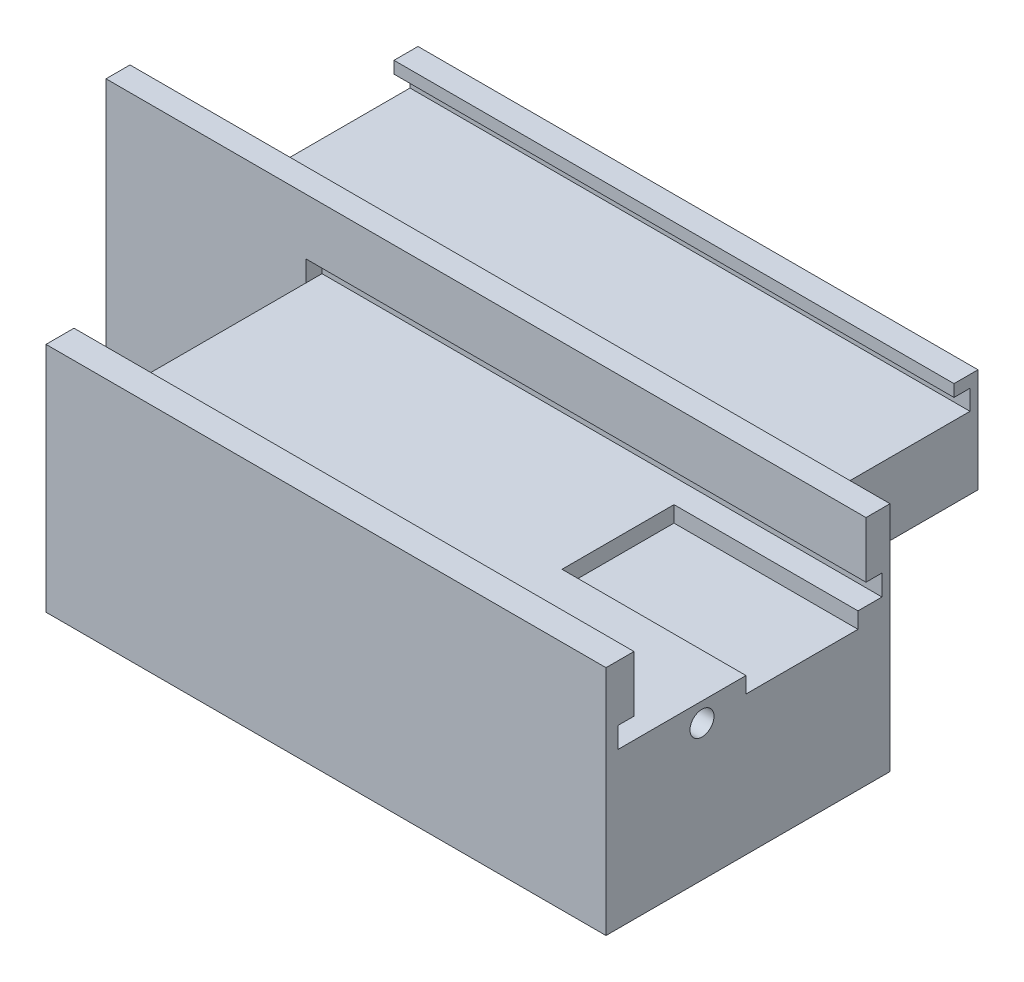
SolidWorks part; units mm, degrees
ref_plane "Front Plane" through (0, 0, 0) normal (0, 0, 1) x (1, 0, 0)
ref_plane "Top Plane" through (0, 0, 0) normal (0, 1, 0) x (1, 0, 0)
ref_plane "Right Plane" through (0, 0, 0) normal (1, 0, 0) x (0, 0, -1)
sketch "Sketch1" plane through (-29.7596, 0, 0) normal (-1, 0, 0) x (0, 0, 1)
  line L0 (-16.3556, -2.2828) -> (-18.3556, -2.2828)
  line L1 (-18.3556, -2.2828) -> (-18.3556, -4.7828)
  line L2 (-18.3556, -4.7828) -> (18.6444, -4.7828)
  line L3 (18.6444, -4.7828) -> (18.6444, -2.2828)
  line L4 (18.6444, -2.2828) -> (16.6444, -2.2828)
  line L10 (50.6443, 5.6172) -> (17.6444, 5.6172)
  line L16 (52.1443, -13.7828) -> (-19.3556, -13.7828)
  line L17 (-19.3556, -13.7828) -> (-19.3556, -0.7828)
  line L18 (-19.3556, -0.7828) -> (-16.3556, -0.7828)
  line L19 (-16.3556, -0.7828) -> (-16.3556, -2.2828)
  line L20 (-15.8556, 15.2172) -> (-15.8556, -2.7828) construction
  line L21 (16.6444, -2.2828) -> (16.6444, 15.2172)
  line L22 (-16.3556, -2.2828) -> (-16.3556, -2.7828) construction
  line L23 (-17.8556, -2.7828) -> (18.1444, -2.7828) construction
  line L24 (-12.9176, -4.2828) -> (-12.9176, -4.7828) construction
  line L25 (-17.8556, -4.2828) -> (18.1444, -4.2828) construction
  line L26 (-18.3556, -3.5328) -> (-17.8556, -3.5328) construction
  line L27 (-17.8556, -2.7828) -> (-17.8556, -4.2828) construction
  line L28 (18.1444, -3.5328) -> (18.6444, -3.5328) construction
  line L29 (18.1444, -2.7828) -> (18.1444, -4.2828) construction
  line L30 (17.1704, -2.2828) -> (17.1704, -2.7828) construction
  line L31 (-16.3556, -0.7705) -> (-15.8556, -0.7705) construction
  line L32 (16.1444, 1.5351) -> (16.6444, 1.5351) construction
  line L33 (16.1444, 15.2172) -> (16.1444, -2.7828) construction
  line L34 (19.2879, 8.2172) -> (19.2879, 7.7172) construction
  line L35 (18.1444, 7.7172) -> (50.1443, 7.7172) construction
  line L36 (50.6443, 5.6172) -> (50.6443, 8.2172)
  line L38 (24.3346, 6.1172) -> (24.3346, 5.6172) construction
  line L39 (50.1443, 6.1172) -> (18.1444, 6.1172) construction
  line L40 (48.848, 8.2172) -> (48.848, 7.7172) construction
  line L41 (16.6444, 15.2172) -> (19.6444, 15.2172)
  line L42 (19.6444, 15.2172) -> (19.6444, 8.2172)
  line L43 (19.6444, 8.2172) -> (17.6444, 8.2172)
  line L44 (17.6444, 8.2172) -> (17.6444, 5.6172)
  line L45 (18.1444, 6.6167) -> (17.6444, 6.6167) construction
  line L46 (18.1444, 6.1172) -> (18.1444, 7.7172) construction
  line L47 (50.6443, 8.2172) -> (48.6443, 8.2172)
  line L48 (48.6443, 8.2172) -> (48.6443, 15.2172)
  line L49 (48.6443, 15.2172) -> (52.1443, 15.2172)
  line L50 (52.1443, 15.2172) -> (52.1443, -13.7828)
  line L51 (50.1443, 6.4526) -> (50.6443, 6.4526) construction
  line L52 (50.1443, 6.1172) -> (50.1443, 7.7172) construction
  dimension "D1" = 0.5
  dimension "D2" = 1.5
  dimension "D3" = 1
  dimension "D4" = 0.5
  dimension "D5" = 9
  dimension "D6" = 29
  dimension "D7" = 1.5
extrude "Boss-Extrude1" add sketch "Sketch1" against normal up to surface (94.9999 mm away)
sketch "Sketch2" plane through (0, 5.6172, 0) normal (0, 1, 0) x (1, 0, 0)
  line L0 (65.2403, -50.6443) -> (65.2403, -17.6444) construction
  line L1 (65.2403, -20.6444) -> (42.2403, -20.6444)
  line L2 (65.2403, -20.6444) -> (65.2403, -34.6444)
  line L3 (65.2403, -34.6444) -> (42.2403, -34.6444)
  line L4 (42.2403, -20.6444) -> (42.2403, -34.6444)
  line L5 (65.2403, -18.6444) -> (-29.7596, -18.6444) construction
  dimension "D1" = 2
  dimension "D2" = 23
  dimension "D3" = 14
extrude "Cut-Extrude1" cut sketch "Sketch2" against normal blind 2
sketch "Sketch4" plane through (0, -0.7828, 0) normal (0, 1, 0) x (1, 0, 0)
  line L1 (-29.7596, -52.1443) -> (-4.7596, -52.1443)
  line L2 (-29.7596, -52.1443) -> (-29.7596, -19.6444)
  line L3 (-29.7596, -19.6444) -> (-4.7596, -19.6444)
  line L4 (-4.7596, -52.1443) -> (-4.7596, -19.6444)
  line L5 (65.2403, 19.3556) -> (40.2404, 19.3556)
  line L6 (65.2403, 19.3556) -> (65.2403, -16.6444)
  line L7 (65.2403, -16.6444) -> (40.2404, -16.6444)
  line L8 (40.2404, 19.3556) -> (40.2404, -16.6444)
  line L9 (40.2404, -18.1444) -> (40.2404, 17.8556) construction
  line L10 (65.2403, -16.6444) -> (-29.7596, -16.6444) construction
  line L11 (65.2403, -19.6444) -> (-29.7596, -19.6444) construction
  line L12 (-4.7596, -50.1443) -> (-4.7596, -18.1454) construction
  point P11 (40.2404, -16.6444)
  point P16 (-4.7596, -19.6444)
extrude "Cut-Extrude2" cut sketch "Sketch4" against normal through all both and the other way through all
sketch "Sketch5" plane through (0, 0, 19.6444) normal (0, 0, 1) x (1, 0, 0)
  line L1 (-29.7596, 8.2172) -> (-4.7596, 8.2172)
  line L2 (-29.7596, 8.2172) -> (-29.7596, 5.6172)
  line L3 (-29.7596, 5.6172) -> (-4.7596, 5.6172)
  line L4 (-4.7596, 8.2172) -> (-4.7596, 5.6172)
  point P6 (0, 0)
extrude "Boss-Extrude3" add sketch "Sketch5" against normal up to surface (2 mm away) up to face at (17.7404, 6.9172, 17.6444)
sketch "Sketch6" plane through (0, 0, 16.6444) normal (0, 0, -1) x (-1, 0, 0)
  line L1 (-40.2404, -2.2828) -> (-65.2403, -2.2828)
  line L2 (-40.2404, -2.2828) -> (-40.2404, -4.7828)
  line L3 (-40.2404, -4.7828) -> (-65.2403, -4.7828)
  line L4 (-65.2403, -2.2828) -> (-65.2403, -4.7828)
extrude "Boss-Extrude4" add sketch "Sketch6" against normal up to surface (2 mm away) up to face at (17.7404, -3.5328, 18.6444)
sketch "Sketch7" plane through (65.2403, 0, 0) normal (1, 0, 0) x (0, 0, -1)
  line L3 (-52.1443, -13.7828) -> (-52.1443, 15.2172) construction
  line L5 (-50.6443, 5.6172) -> (-34.6444, 5.6172) construction
  circle A0 centre (-40.1443, 3.2172) radius 1.5
  point P0 (-39.4058, 2.254)
  point P8 (0, 0)
  point P9 (-34.3944, 0.347)
  dimension "D1" = 2.4
  dimension "3" = 3
  dimension "D3" = 12
extrude "Cut-Extrude3" cut sketch "Sketch7" against normal blind 10
sketch "Sketch8" plane through (-29.7596, 0, 0) normal (-1, 0, 0) x (0, 0, 1)
  line L0 (18.6444, -4.7828) -> (-18.3556, -4.7828) construction
  line L1 (-19.3556, -7.1828) -> (16.6444, -7.1828) construction
  line L2 (-19.3556, -0.7828) -> (-19.3556, -13.7828) construction
  line L3 (16.6444, -13.7828) -> (16.6444, -4.7828) construction
  circle A0 centre (-1.3556, -7.1828) radius 1.5
  circle A1 centre (40.1443, 3.2172) radius 1.5 construction
  point P12 (-1.3556, -7.2828)
  point P13 (0, 0)
  point P14 (-1.3556, -7.1828)
  dimension "D1" = 2.4
extrude "Cut-Extrude4" cut sketch "Sketch8" against normal blind 10
